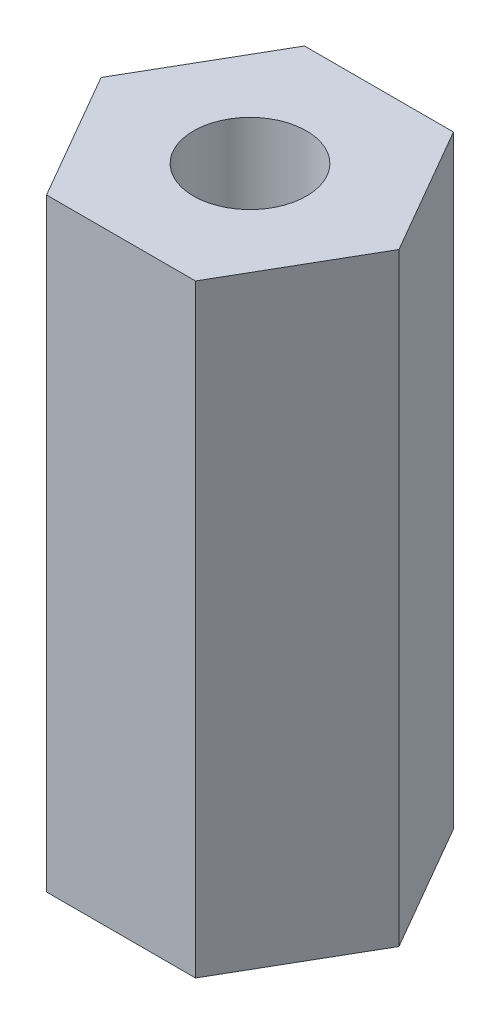
SolidWorks part; units mm, degrees
material "Brass"
ref_plane "Front" through (0, 0, 0) normal (0, 0, 1) x (1, 0, 0)
ref_plane "Top" through (0, 0, 0) normal (0, 1, 0) x (1, 0, 0)
ref_plane "Right" through (0, 0, 0) normal (1, 0, 0) x (0, 0, -1)
sketch "Sketch1" plane through (0, 0, 0) normal (0, 1, 0) x (1, 0, 0)
  line L1 (2.702, 0) -> (1.351, 2.34)
  line L2 (1.351, 2.34) -> (-1.351, 2.34)
  line L3 (-1.351, 2.34) -> (-2.702, 0)
  line L4 (-2.702, 0) -> (-1.351, -2.34)
  line L5 (-1.351, -2.34) -> (1.351, -2.34)
  line L6 (1.351, -2.34) -> (2.702, 0)
  circle A0 centre (0, 0) radius 2.34 construction
  dimension "D1" = 4.68
extrude "Boss-Extrude1" add sketch "Sketch1" along normal blind 10.95
hole_wizard "Ø2.05 (2.05) Diameter Hole1" positions "Sketch4" profile "Sketch3" hole size "Ø2.05" standard "ANSI Metric" end condition through all
sketch "Sketch4" plane through (0, 10.95, 0) normal (0, 1, 0) x (1, 0, 0)
  point P0 (0, 0)
sketch "Sketch3" plane through (0, 10.95, 0) normal (1, 0, 0) x (0, 0, 1)
  line L0 (0, 0) -> (0, 10.95)
  line L1 (0, 10.95) -> (1.025, 10.95)
  line L2 (1.025, 10.95) -> (1.025, 0)
  line L5 (1.025, 0) -> (0, 0)
  line L11 (0, -6.35) -> (0, 107.95) construction
  dimension "Thru Hole Dia." = 2.05
  dimension "Thru Hole Depth" = 10.95
